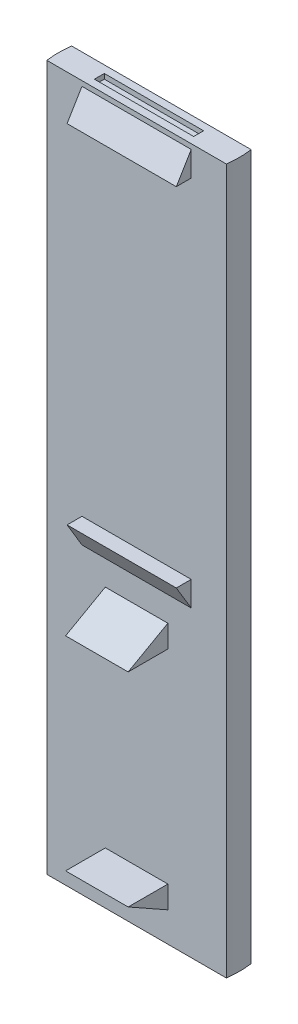
SolidWorks part; units mm, degrees
ref_plane "Front Plane" through (0, 0, 0) normal (0, 0, 1) x (1, 0, 0)
ref_plane "Top Plane" through (0, 0, 0) normal (0, 1, 0) x (1, 0, 0)
ref_plane "Right Plane" through (0, 0, 0) normal (1, 0, 0) x (0, 0, -1)
sketch "Sketch1" plane through (0, 0, 0) normal (0, 0, 1) x (1, 0, 0)
  line L1 (49.53, -180.34) -> (-49.53, -180.34)
  line L2 (49.53, -180.34) -> (49.53, 180.34)
  line L3 (49.53, 180.34) -> (-49.53, 180.34)
  line L4 (-49.53, -180.34) -> (-49.53, 180.34)
  line L5 (49.53, -180.34) -> (-49.53, 180.34) construction
  line L6 (49.53, 180.34) -> (-49.53, -180.34) construction
  point P0 (0, 0)
  dimension "D1" = 360.68
  dimension "D2" = 99.06
extrude "Boss-Extrude1" add sketch "Sketch1" along normal blind 12.7
sketch "Sketch2" plane through (0, 0, 12.7) normal (0, 0, 1) x (1, 0, 0)
  line L0 (0, 180.34) -> (0, -230.2299) construction
  line L2 (49.53, 180.34) -> (-49.53, 180.34) construction
  line L4 (-49.53, 0) -> (49.53, 0) construction
  line L10 (27.94, -25.4) -> (-27.94, -25.4)
  line L15 (27.94, -25.4) -> (27.94, 177.8)
  line L16 (27.94, 177.8) -> (-27.94, 177.8)
  line L17 (49.53, -180.34) -> (49.53, 180.34) construction
  line L18 (-27.94, -25.4) -> (-27.94, 177.8)
  line L19 (27.94, -25.4) -> (-27.94, 177.8) construction
  line L20 (27.94, 177.8) -> (-27.94, -25.4) construction
  line L21 (27.94, -12.7) -> (-27.94, -12.7)
  line L22 (27.94, -12.7) -> (27.94, 165.1)
  line L23 (27.94, 165.1) -> (-27.94, 165.1)
  line L24 (-27.94, -12.7) -> (-27.94, 165.1)
  line L25 (27.94, -12.7) -> (-27.94, 165.1) construction
  line L26 (27.94, 165.1) -> (-27.94, -12.7) construction
  point P1 (0, 76.2)
  point P15 (0, 76.2)
  dimension "D1" = 76.2
  dimension "D2" = 203.2
  dimension "D3" = 177.8
  dimension "D4" = 55.88
sketch "Sketch3" plane through (0, 0, 0) normal (0, 0, -1) x (-1, 0, 0)
  line L0 (0, -180.34) -> (0, 180.34) construction
  line L1 (-49.53, 180.34) -> (49.53, 180.34) construction
  line L2 (49.53, 0) -> (-49.53, 0) construction
  line L3 (-49.53, -180.34) -> (-49.53, 180.34) construction
  line L11 (16.002, -165.1) -> (-16.002, -165.1)
  line L12 (16.002, -165.1) -> (16.002, -38.1)
  line L13 (16.002, -38.1) -> (-16.002, -38.1)
  line L14 (-16.002, -165.1) -> (-16.002, -38.1)
  line L15 (16.002, -165.1) -> (-16.002, -38.1) construction
  line L16 (16.002, -38.1) -> (-16.002, -165.1) construction
  line L23 (16.002, -153.67) -> (-16.002, -153.67)
  line L24 (16.002, -153.67) -> (16.002, -49.53)
  line L25 (16.002, -49.53) -> (-16.002, -49.53)
  line L26 (-16.002, -153.67) -> (-16.002, -49.53)
  line L27 (16.002, -153.67) -> (-16.002, -49.53) construction
  line L28 (16.002, -49.53) -> (-16.002, -153.67) construction
  point P6 (0, 0)
  point P12 (0, 0)
  point P17 (0, -101.6)
  point P26 (0, -101.6)
  dimension "D1" = 127
  dimension "D2" = 32.004
  dimension "D5" = 101.6
  dimension "D7" = 104.14
extrude "Boss-Extrude3" add sketch "Sketch3" along normal blind 20.32 contours L25 L12 L13 L14 | L12 L23 L14 L11
extrude "Boss-Extrude4" add sketch "Sketch2" along normal mid plane 15.24 contours L23 L15 L16 L18 | L15 L21 L18 L10
ref_plane "Plane2" through (0, 0, 6.35) normal (0, 0, 1) x (1, 0, 0)
mirror "Mirror1" about plane through (0, 0, 6.35) normal (0, 0, 1) of "Boss-Extrude3"
sketch "Sketch5" plane through (0, 0, 0) normal (1, 0, 0) x (0, 0, -1)
  line L0 (-12.7, -180.34) -> (0, -180.34) construction
  line L1 (-12.7, 180.34) -> (0, 180.34) construction
  line L2 (-12.7, 180.34) -> (-12.7, -180.34) construction
  line L3 (-12.7, -180.34) -> (0, -180.34) construction
  line L5 (-20.32, 165.1) -> (-12.7, 165.1) construction
  line L6 (20.32, -153.67) -> (0, -153.67) construction
  line L7 (20.32, -153.67) -> (20.32, -165.1) construction
  line L8 (20.32, -165.1) -> (0, -165.1) construction
  line L9 (0, -153.67) -> (0, -165.1) construction
  line L10 (-33.02, -153.67) -> (-12.7, -153.67) construction
  line L11 (-33.02, -153.67) -> (-33.02, -165.1) construction
  line L12 (-33.02, -165.1) -> (-12.7, -165.1) construction
  line L13 (-12.7, -153.67) -> (-12.7, -165.1) construction
  line L14 (20.32, -38.1) -> (0, -38.1) construction
  line L15 (20.32, -38.1) -> (20.32, -49.53) construction
  line L16 (20.32, -49.53) -> (0, -49.53) construction
  line L17 (0, -38.1) -> (0, -49.53) construction
  line L18 (-33.02, -38.1) -> (-12.7, -38.1) construction
  line L19 (-33.02, -38.1) -> (-33.02, -49.53) construction
  line L20 (-33.02, -49.53) -> (-12.7, -49.53) construction
  line L21 (-12.7, -38.1) -> (-12.7, -49.53) construction
  line L25 (-12.7, -12.7) -> (-12.7, 0) construction
  line L26 (-20.32, 177.8) -> (-12.7, 177.8) construction
  line L27 (-20.32, 177.8) -> (-20.32, 165.1) construction
  line L28 (-20.32, 165.1) -> (-12.7, 165.1) construction
  line L29 (-12.7, 177.8) -> (-12.7, 165.1) construction
  line L30 (0, 180.34) -> (0, -180.34) construction
  line L31 (20.32, -153.67) -> (0, -165.1)
  line L32 (0, -165.1) -> (20.32, -165.1)
  line L33 (20.32, -165.1) -> (20.32, -153.67)
  line L34 (-33.02, -153.67) -> (-12.7, -165.1)
  line L35 (-12.7, -165.1) -> (-33.02, -165.1)
  line L36 (-33.02, -165.1) -> (-33.02, -153.67)
  line L37 (-33.02, -49.53) -> (-33.02, -38.1)
  line L38 (-33.02, -38.1) -> (-12.7, -38.1)
  line L39 (-12.7, -38.1) -> (-33.02, -49.53)
  line L40 (20.32, -49.53) -> (0, -38.1)
  line L41 (0, -38.1) -> (20.32, -38.1)
  line L42 (20.32, -38.1) -> (20.32, -49.53)
  line L46 (-12.7, 177.8) -> (-20.32, 165.1)
  line L47 (-20.32, 165.1) -> (-20.32, 177.8)
  line L48 (-20.32, 177.8) -> (-12.7, 177.8)
  line L49 (-12.7, -12.7) -> (-20.32, -12.7) construction
  line L50 (-20.32, -12.7) -> (-20.32, -25.4) construction
  line L51 (-20.32, -25.4) -> (-12.7, -25.4) construction
  line L52 (-20.32, -12.7) -> (-12.7, -25.4)
  line L53 (-12.7, -25.4) -> (-20.32, -25.4)
  line L54 (-20.32, -25.4) -> (-20.32, -12.7)
extrude "Cut-Extrude2" cut sketch "Sketch5" against normal mid plane 76.2
sketch "Sketch6" plane through (0, 180.34, 0) normal (0, 1, 0) x (1, 0, 0)
  line L0 (0, 0) -> (0, -12.7) construction
  line L1 (-49.53, -12.7) -> (49.53, -12.7) construction
  line L2 (-49.53, -12.7) -> (-49.53, 0) construction
  line L3 (-49.53, 0) -> (49.53, 0) construction
  line L4 (49.53, -12.7) -> (49.53, 0) construction
  line L5 (-49.53, -6.35) -> (49.53, -6.35) construction
  line L7 (25.4, -8.89) -> (-25.4, -8.89)
  line L8 (25.4, -8.89) -> (25.4, -3.81)
  line L9 (25.4, -3.81) -> (-25.4, -3.81)
  line L10 (-25.4, -8.89) -> (-25.4, -3.81)
  line L11 (25.4, -8.89) -> (-25.4, -3.81) construction
  line L12 (25.4, -3.81) -> (-25.4, -8.89) construction
  point P10 (0, -6.35)
  dimension "D1" = 5.08
  dimension "D2" = 50.8
extrude "Cut-Extrude3" cut sketch "Sketch6" against normal blind 2.54
mirror "Mirror2" about plane through (0, 0, 0) normal (0, 1, 0) of "Cut-Extrude3"
sketch "Sketch7" plane through (0, 180.34, 0) normal (0, 1, 0) x (1, 0, 0)
  line L0 (-49.53, -6.35) -> (49.53, -6.35) construction
  line L1 (-49.53, -12.7) -> (-49.53, 0) construction
  line L2 (49.53, -12.7) -> (49.53, 0) construction
  line L3 (0, 0) -> (0, -12.7) construction
  line L4 (-16.002, 0) -> (16.002, 0) construction
  line L5 (-27.94, -12.7) -> (27.94, -12.7) construction
  circle A0 centre (0, -6.35) radius 46.355
  circle A1 centre (0, -6.35) radius 50.8
  dimension "D1" = 92.71
  dimension "D2" = 101.6
extrude "Cut-Extrude4" cut sketch "Sketch7" against normal through all
